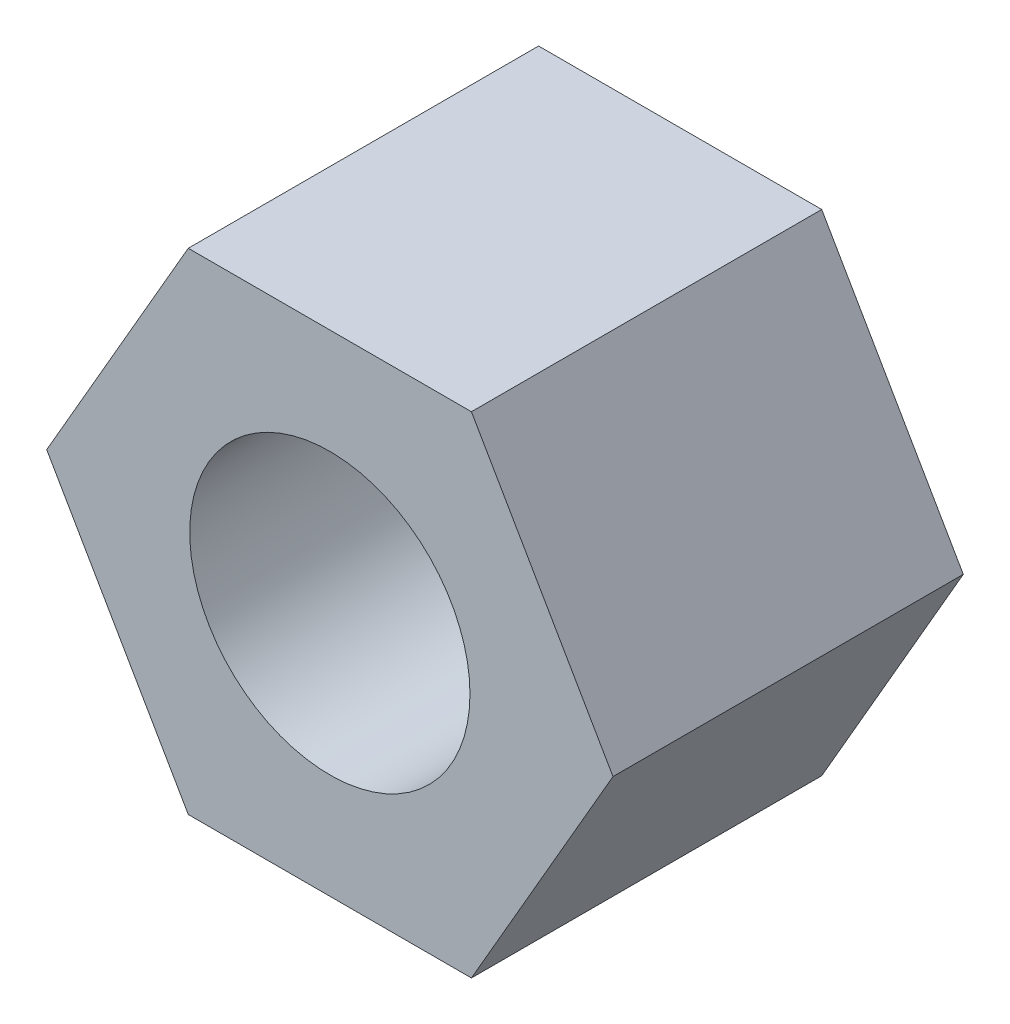
SolidWorks part; units mm, degrees
ref_plane "Front Plane" through (0, 0, 0) normal (0, 0, 1) x (1, 0, 0)
ref_plane "Top Plane" through (0, 0, 0) normal (0, 1, 0) x (1, 0, 0)
ref_plane "Right Plane" through (0, 0, 0) normal (1, 0, 0) x (0, 0, -1)
sketch "Sketch1" plane through (0, 0, 0) normal (0, 0, 1) x (1, 0, 0)
  line L1 (-40.4145, 0) -> (-20.2073, -35)
  line L2 (-20.2073, -35) -> (20.2073, -35)
  line L3 (20.2073, -35) -> (40.4145, 0)
  line L4 (40.4145, 0) -> (20.2073, 35)
  line L5 (20.2073, 35) -> (-20.2073, 35)
  line L6 (-20.2073, 35) -> (-40.4145, 0)
extrude "Boss-Extrude1" add sketch "Sketch1" along normal blind 50
sketch "Sketch2" plane through (0, 0, 50) normal (0, 0, 1) x (1, 0, 0)
  circle A0 centre (0, 0) radius 20
extrude "Cut-Extrude1" cut sketch "Sketch2" against normal blind 50
